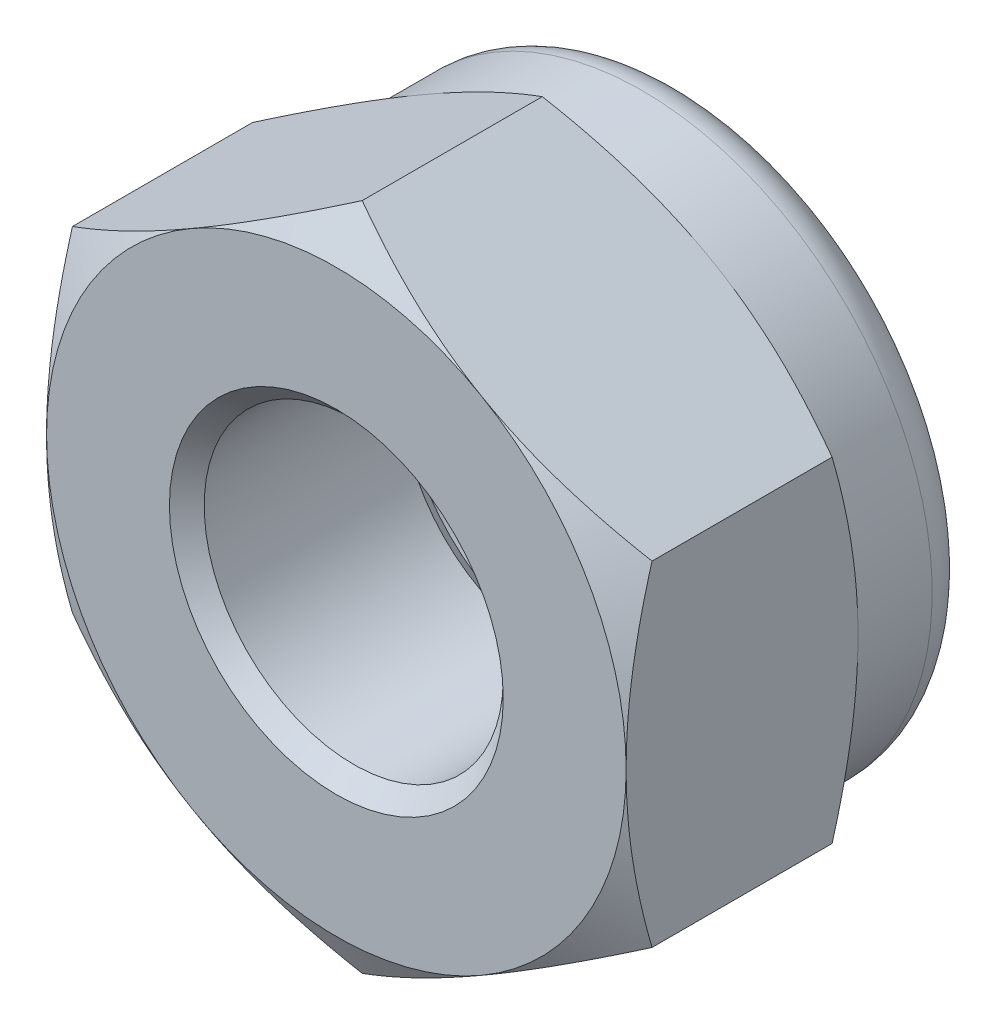
SolidWorks part; units mm, degrees
ref_plane "前视基准面" through (0, 0, 0) normal (0, 0, 1) x (1, 0, 0)
ref_plane "上视基准面" through (0, 0, 0) normal (0, 1, 0) x (1, 0, 0)
ref_plane "右视基准面" through (0, 0, 0) normal (1, 0, 0) x (0, 0, -1)
sketch "草图1" plane through (0, 0, 0) normal (0, 0, 1) x (1, 0, 0)
  line L1 (0, 5.7735) -> (-5, 2.8868)
  line L2 (-5, 2.8868) -> (-5, -2.8868)
  line L3 (-5, -2.8868) -> (0, -5.7735)
  line L4 (0, -5.7735) -> (5, -2.8868)
  line L5 (5, -2.8868) -> (5, 2.8868)
  line L6 (5, 2.8868) -> (0, 5.7735)
  circle A0 centre (0, 0) radius 5 construction
  circle A1 centre (0, 0) radius 2.58
  dimension "D1" = 5.16
  dimension "D2" = 10
extrude "凸台-拉伸1" add sketch "草图1" against normal blind 4
cosmetic thread "装饰螺纹线1" parameters "D1"=4, "D2"=6
sketch "草图2" plane through (0, 0, 0) normal (1, 0, 0) x (0, 0, -1)
  line L0 (0, 5) -> (0.4466, 5.7735)
  line L1 (0, 2.8868) -> (0, 5.7735) construction
  line L2 (4, 5.7735) -> (0, 5.7735) construction
  line L3 (0.4466, 5.7735) -> (0, 5.7735)
  line L4 (0, 5.7735) -> (0, 5)
  line L5 (0, 0) -> (4, 0) construction
  line L6 (4, -2.8868) -> (4, 2.8868) construction
  line L7 (4, 5) -> (3.5534, 5.7735)
  line L8 (4, 2.8868) -> (4, 5.7735) construction
  line L9 (3.5534, 5.7735) -> (4, 5.7735)
  line L10 (4, 5.7735) -> (4, 5)
  dimension "D1" = 10
  dimension "D2" = 30
revolve "切除-旋转1" cut sketch "草图2" angle 360 about L5
chamfer "倒角1" [suppressed] distance 0.3 angle 45
sketch "草图3" [suppressed] plane through (0, 0, 0) normal (0, 0, 1) x (1, 0, 0)
  circle A0 centre (0, 0) radius 2.4
  circle A1 centre (0, 0) radius 3.5
  dimension "D1" = 7.2
extrude "凸台-拉伸2" [suppressed] add sketch "草图3" along normal blind 2
fillet "圆角1" [suppressed] radius 0.3
sketch "草图4" [suppressed] plane through (0, 0, 0) normal (0, 0, 1) x (1, 0, 0)
  line L0 (-1.72, 0) -> (-1.9596, 0)
  line L1 (-0.86, 1.4896) -> (-0.9798, 1.6971)
  arc A0 (-1.9596, 0) -> (-2.3515, 0.48) centre (-1.9596, 0.4) cw
  arc A1 (-1.5914, 1.7965) -> (-0.9798, 1.6971) centre (-1.3262, 1.4971) cw
  circle A3 centre (0, 0) radius 2.4 construction
  arc A4 (-1.5914, 1.7965) -> (-2.3515, 0.48) centre (0, 0) ccw
  arc A5 (-0.86, 1.4896) -> (-1.72, 0) centre (0, 0) ccw
  point P4 (-2.4, 0)
  dimension "D1" = 5.16
  dimension "D3" = 0.6
  dimension "D2" = 60
extrude "凸台-拉伸3" [suppressed] add sketch "草图4" along normal blind 1
pattern_circular "阵列(圆周)1" [suppressed] count 3 over 360
sketch "草图5" plane through (0, 0, -4) normal (0, 0, -1) x (-1, 0, 0)
  circle A0 centre (0, 0) radius 5
  circle A2 centre (0, 0) radius 3.3
  dimension "D1" = 6.6
extrude "凸台-拉伸4" add sketch "草图5" along normal blind 2
fillet "圆角2" radius 0.72 1 edges at (-5, 0, -6)
sketch "草图6" plane through (0, 0, -6) normal (0, 0, -1) x (-1, 0, 0)
  circle A0 centre (0, 0) radius 3.75
  dimension "D1" = 7.5
extrude "切除-拉伸1" cut sketch "草图6" against normal blind 0.5
chamfer "倒角2" distance 0.3 angle 45 2 edges at (2.58, 0, 0) (2.58, 0, -4)
equation "\"S\"=10"
equation "\"M\"=6"
equation "\"H\"=6"
equation "\"m_\"=4"
equation "\"D1@草图1\"  = \"M\" * .86"
equation "\"D2@草图1\" = \"S\""
equation "\"D1@凸台-拉伸1\"=\"m_\""
equation "\"D1@草图2\"=\"S\""
equation "\"D1@倒角1\"=\"M\"*.05"
equation "\"D1@草图3\"=\"M\"*1.2"
equation "\"D1@凸台-拉伸2\" = \"H\" - \"m_\""
equation "\"D1@圆角1\"=\"M\"*.05"
equation "\"D1@草图4\"=\"M\" * .86"
equation "\"D2@草图4\"  = \"AN\""
equation "\"D1@阵列(圆周)1\" = 180 / \"AN\""
equation "\"D1@凸台-拉伸3\"= \"H\" *.5- \"m_\"*.5"
equation "\"D2@装饰螺纹线1\"=\"M\""
equation "\"D1@草图5\"=\"M\"*1.1"
equation "\"D1@凸台-拉伸4\"= \"H\" - \"m_\""
equation "\"D1@圆角2\"=\"M\"*.12"
equation "\"D1@草图6\"=\"M\"*1.25"
equation "\"D1@切除-拉伸1\"= \"H\"*.25 - \"m_\"*.25"
equation "\"AN\"=60"
equation "\"D1@装饰螺纹线1\" = \"m_\""
equation "\"D1@倒角2\"=\"M\"*0.05"
equation "\"D3@草图4\"=\"M\"*0.1"
